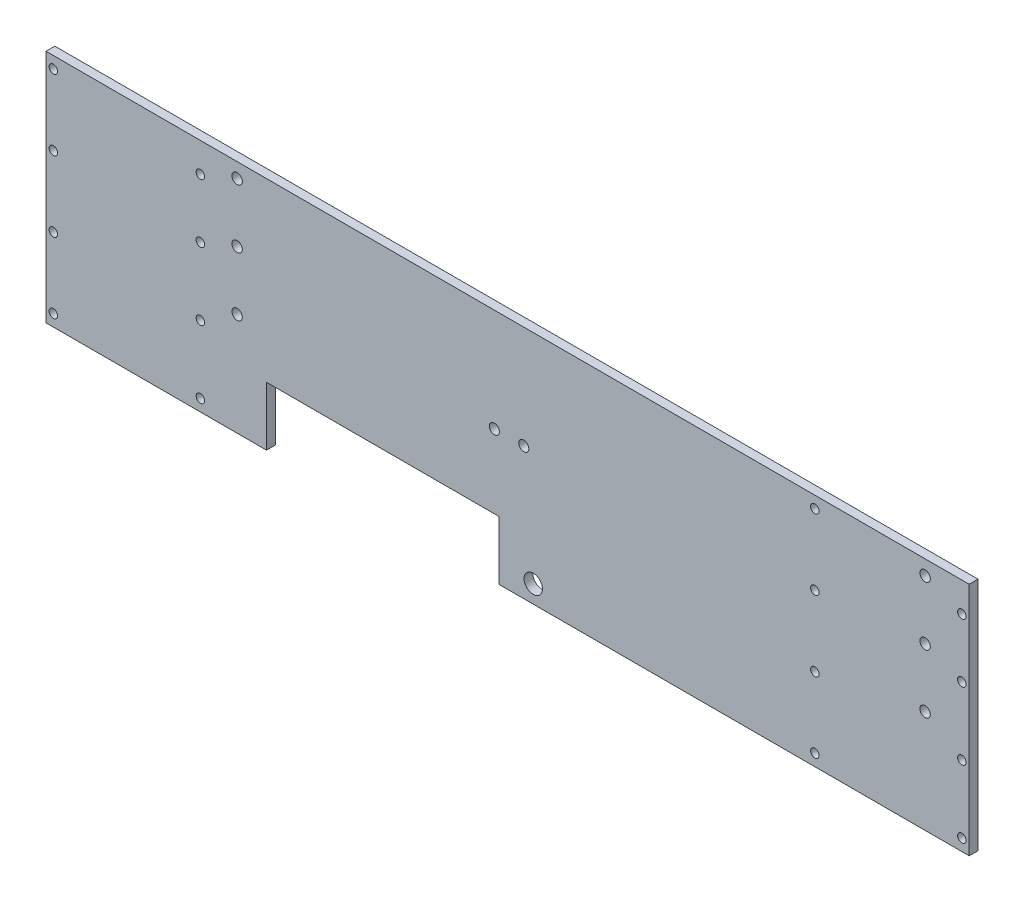
SolidWorks part; units mm, degrees
material "6061-T6 (SS)"
ref_plane "Front Plane" through (0, 0, 0) normal (0, 0, 1) x (1, 0, 0)
ref_plane "Top Plane" through (0, 0, 0) normal (0, 1, 0) x (1, 0, 0)
ref_plane "Right Plane" through (0, 0, 0) normal (1, 0, 0) x (0, 0, -1)
sketch "Sketch1" plane through (0, 0, 0) normal (0, 0, 1) x (1, 0, 0)
  line L1 (-199.39, 50.8) -> (199.39, 50.8)
  line L2 (-199.39, 50.8) -> (-199.39, -50.8)
  line L3 (-199.39, -50.8) -> (199.39, -50.8)
  line L4 (199.39, 50.8) -> (199.39, -50.8)
  line L5 (-199.39, 50.8) -> (199.39, -50.8) construction
  line L6 (-199.39, -50.8) -> (199.39, 50.8) construction
  point P0 (0, 0)
  dimension "D1" = 101.6
  dimension "D2" = 398.78
extrude "Boss-Extrude1" add sketch "Sketch1" along normal blind 3.81
sketch "Sketch11" plane through (0, 0, 3.81) normal (0, 0, 1) x (1, 0, 0)
  line L0 (-199.39, -50.8) -> (199.39, -50.8) construction
  line L1 (-104.14, -50.8) -> (-3.81, -50.8)
  line L2 (-104.14, -50.8) -> (-104.14, -25.4)
  line L3 (-104.14, -25.4) -> (-3.81, -25.4)
  line L4 (-3.81, -50.8) -> (-3.81, -25.4)
  line L5 (-199.39, 50.8) -> (-199.39, -50.8) construction
  line L6 (199.39, -50.8) -> (199.39, 50.8) construction
  dimension "D1" = 25.4
  dimension "D2" = 95.25
  dimension "D3" = 203.2
extrude "Cut-Extrude1" cut sketch "Sketch11" against normal through all
sketch "Sketch12" plane through (0, 0, 3.81) normal (0, 0, 1) x (1, 0, 0)
  line L0 (-3.81, -50.8) -> (-3.81, -25.4) construction
  line L1 (-3.81, -50.8) -> (199.39, -50.8) construction
  point P0 (11.0749, -43.18)
  dimension "D1" = 14.8849
  dimension "D2" = 7.62
hole_wizard "5/16 (0.3125) Diameter Hole1" positions "Sketch13" profile "Sketch14" hole size "5/16" standard "ANSI Inch" end condition through all
sketch "Sketch13" plane through (0, 0, 3.81) normal (0, 0, 1) x (1, 0, 0)
  point P0 (11.0749, -43.18)
sketch "Sketch14" plane through (11.0749, -43.18, 3.81) normal (1, 0, 0) x (0, -1, 0)
  line L0 (0, 0) -> (0, 3.81)
  line L1 (0, 3.81) -> (3.9687, 3.81)
  line L2 (3.9687, 3.81) -> (3.9687, 0)
  line L5 (3.9687, 0) -> (0, 0)
  line L11 (0, -6.35) -> (0, 107.95) construction
  dimension "Thru Hole Dia." = 7.9375
  dimension "Thru Hole Depth" = 3.81
sketch "Sketch15" plane through (0, 0, 3.81) normal (0, 0, 1) x (1, 0, 0)
  line L0 (199.39, 50.8) -> (-199.39, 50.8) construction
  line L2 (180.34, 44.45) -> (180.34, -6.35) construction
  line L3 (199.39, -50.8) -> (199.39, 50.8) construction
  line L4 (199.39, 50.8) -> (-199.39, 50.8) construction
  point P0 (196.215, 38.1)
  point P1 (196.215, 12.7)
  point P2 (196.215, -16.51)
  point P3 (196.215, -45.72)
  point P9 (132.715, -45.72)
  point P10 (180.34, 19.05)
  point P11 (132.715, -15.24)
  point P12 (132.715, 15.24)
  point P13 (132.715, 45.72)
  dimension "D1" = 63.5
  dimension "D2" = 3.175
  dimension "D3" = 29.21
  dimension "D4" = 29.21
  dimension "D5" = 25.4
  dimension "D6" = 5.08
  dimension "D7" = 30.48
  dimension "D8" = 30.48
  dimension "D9" = 30.48
  dimension "D10" = 19.05
  dimension "D11" = 50.8
  dimension "D12" = 6.35
hole_wizard "#6 Clearance Hole1" positions "Sketch19" profile "Sketch20" hole size "#6" standard "ANSI Inch" end condition through all
sketch "Sketch19" plane through (0, 0, 3.81) normal (0, 0, 1) x (1, 0, 0)
  point P18 (132.715, -15.24)
  point P21 (196.215, -16.51)
  point P24 (196.215, 12.7)
  point P27 (196.215, 38.1)
  point P30 (132.715, 45.72)
  point P33 (132.715, 15.24)
  point P55 (132.715, -45.72)
  point P58 (196.215, -45.72)
sketch "Sketch20" plane through (132.715, -15.24, 3.81) normal (1, 0, 0) x (0, -1, 0)
  line L0 (0, 0) -> (0, 3.81)
  line L1 (0, 3.81) -> (1.8288, 3.81)
  line L2 (1.8288, 3.81) -> (1.8288, 0)
  line L5 (1.8288, 0) -> (0, 0)
  line L11 (0, -6.35) -> (0, 107.95) construction
  dimension "Thru Hole Dia." = 3.6576
  dimension "Thru Hole Depth" = 3.81
hole_wizard "#8 Clearance Hole1" positions "Sketch24" profile "Sketch25" hole size "#8" standard "ANSI Inch" end condition through all
sketch "Sketch24" plane through (0, 0, 3.81) normal (0, 0, 1) x (1, 0, 0)
  line L0 (-199.39, 50.8) -> (-199.39, -50.8) construction
  point P0 (180.34, 44.45)
  point P3 (180.34, 19.05)
  point P6 (180.34, -6.35)
  point P10 (-116.84, 44.45)
  point P12 (-116.84, 19.05)
  point P14 (-116.84, -6.35)
  point P19 (0, 0)
  point P20 (0, 0)
  point P21 (0, 0)
  point P22 (0, 0)
  dimension "D1" = 82.55
sketch "Sketch25" plane through (180.34, 44.45, 3.81) normal (1, 0, 0) x (0, -1, 0)
  line L0 (0, 0) -> (0, 3.81)
  line L1 (0, 3.81) -> (2.2479, 3.81)
  line L2 (2.2479, 3.81) -> (2.2479, 0)
  line L5 (2.2479, 0) -> (0, 0)
  line L11 (0, -6.35) -> (0, 107.95) construction
  dimension "Thru Hole Dia." = 4.4958
  dimension "Thru Hole Depth" = 3.81
pattern_linear "LPattern1" count 2 spacing 328.93 along (-1, 0, 0) of "#6 Clearance Hole1"
sketch "Sketch21" plane through (0, 0, 3.81) normal (0, 0, 1) x (1, 0, 0)
  line L0 (199.39, 50.8) -> (-199.39, 50.8) construction
  line L1 (-199.39, 50.8) -> (-199.39, -50.8) construction
  point P0 (-5.715, 6.35)
  point P5 (6.985, 6.35)
  dimension "D1" = 44.45
  dimension "D2" = 193.675
  dimension "D3" = 44.45
  dimension "D4" = 206.375
hole_wizard "11/64 (0.17188) Diameter Hole2" positions "Sketch22" profile "Sketch23" hole size "11/64" standard "ANSI Inch"
sketch "Sketch22" plane through (0, 0, 3.81) normal (0, 0, 1) x (1, 0, 0)
  point P0 (-5.715, 6.35)
  point P3 (6.985, 6.35)
sketch "Sketch23" plane through (-5.715, 6.35, 3.81) normal (1, 0, 0) x (0, -1, 0)
  line L0 (0, 0) -> (0, 10.2016)
  line L1 (0, 10.2016) -> (2.1829, 8.89)
  line L2 (2.1829, 8.89) -> (2.1829, 0)
  line L5 (2.1829, 0) -> (0, 0)
  line L10 (0, 10.2016) -> (-2.1829, 8.89) construction
  line L11 (0, -6.35) -> (0, 107.95) construction
  dimension "Hole Dia." = 4.3658
  dimension "Hole Depth" = 8.89
  dimension "Drill Angle" = 118
